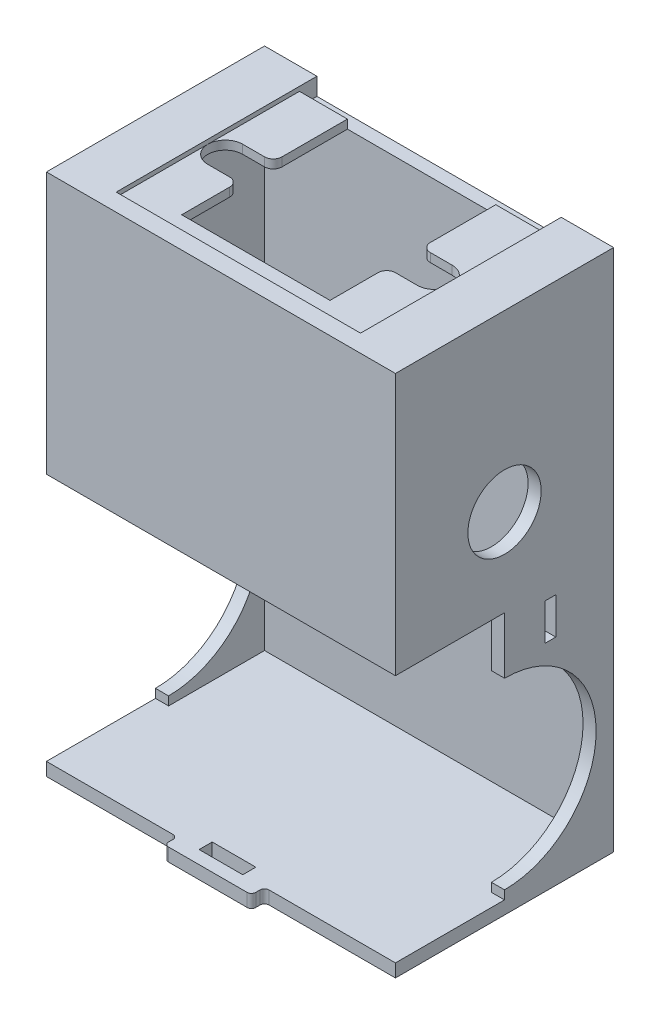
SolidWorks part; units mm, degrees
ref_plane "前视基准面" through (0, 0, 0) normal (0, 0, 1) x (1, 0, 0)
ref_plane "上视基准面" through (0, 0, 0) normal (0, 1, 0) x (1, 0, 0)
ref_plane "右视基准面" through (0, 0, 0) normal (1, 0, 0) x (0, 0, -1)
sketch "草图1" plane through (0, 0, 0) normal (0, 0, 1) x (1, 0, 0)
  line L1 (-20, -30) -> (20, -30)
  line L2 (-20, -30) -> (-20, 30)
  line L3 (-20, 30) -> (20, 30)
  line L4 (20, -30) -> (20, 30)
  line L5 (-20, -30) -> (20, 30) construction
  line L6 (-20, 30) -> (20, -30) construction
  point P0 (0, 0)
  dimension "D1" = 40
  dimension "D2" = 60
extrude "凸台-拉伸1" add sketch "草图1" along normal blind 25
shell "抽壳1" thickness 1.5
sketch "草图2" plane through (20, 0, 0) normal (1, 0, 0) x (0, 0, -1)
  line L0 (-12.5, 30) -> (-12.5, -30) construction
  line L1 (-25, 30) -> (0, 30) construction
  line L2 (-25, -30) -> (0, -30) construction
  circle A0 centre (-12.5, -17) radius 10.5
  dimension "D1" = 13
  dimension "D2" = 21
extrude "切除-拉伸1" cut sketch "草图2" against normal blind 75
sketch "草图3" plane through (0, 0, 25) normal (0, 0, 1) x (1, 0, 0)
  line L0 (20, -30) -> (20, 30) construction
  line L1 (-20, 30) -> (20, 30)
  line L2 (-20, 30) -> (-20, 0)
  line L3 (-20, 0) -> (20, 0)
  line L4 (20, 30) -> (20, 0)
  line L5 (-20, 30) -> (20, 0) construction
  line L6 (-20, 0) -> (20, 30) construction
  line L7 (-20, -30) -> (20, -30) construction
  point P4 (0, 15)
  dimension "D1" = 30
extrude "凸台-拉伸2" add sketch "草图3" against normal blind 1
sketch "草图4" plane through (0, 0, 25) normal (0, 0, 1) x (1, 0, 0)
  line L0 (-20, 30) -> (-20, -30) construction
  line L1 (-20, 0) -> (20, 0)
  line L2 (-20, 0) -> (-20, -28.5)
  line L3 (-20, -28.5) -> (20, -28.5)
  line L4 (20, 0) -> (20, -28.5)
  line L5 (-20, 0) -> (20, -28.5) construction
  line L6 (-20, -28.5) -> (20, 0) construction
  line L7 (20, -30) -> (20, 30) construction
  line L8 (-18.5, 0) -> (18.5, 0) construction
  point P4 (0, -14.25)
  dimension "D1" = 28.5
extrude "切除-拉伸2" cut sketch "草图4" against normal blind 12.5
sketch "草图5" plane through (0, 30, 0) normal (0, 1, 0) x (1, 0, 0)
  line L0 (-30, -12.5) -> (20, -12.5) construction
  line L1 (20, -25) -> (20, 0) construction
  line L3 (20, 0) -> (-20, 0) construction
  circle A1 centre (-20, -12.5) radius 4.2
  circle A2 centre (20, -12.5) radius 4.2
  dimension "D1" = 20
  dimension "D2" = 20
  dimension "D3" = 12.5
extrude "切除-拉伸3" cut sketch "草图5" against normal blind 1.5
sketch "草图6" plane through (0, 30, 0) normal (0, 1, 0) x (1, 0, 0)
  line L0 (0, 5) -> (0, -21) construction
  line L2 (-15.8, -12.5) -> (15.8, -12.5) construction
  line L4 (-14, -21) -> (14, -21)
  line L5 (-14, -21) -> (-14, 5)
  line L6 (-14, 5) -> (14, 5)
  line L7 (14, -21) -> (14, 5)
  line L8 (-14, -21) -> (14, 5) construction
  line L9 (-14, 5) -> (14, -21) construction
  circle A0 centre (0, -12.5) radius 7.5 construction
  circle A1 centre (-20, -12.5) radius 4.2 construction
  circle A2 centre (20, -12.5) radius 4.2 construction
  point P2 (0, -8)
  dimension "D1" = 15
  dimension "D4" = 26
  dimension "D2" = 8.5
  dimension "D5" = 28
extrude "切除-拉伸4" cut sketch "草图6" against normal blind 0.5
sketch "草图8" plane through (0, 29.5, 0) normal (0, 1, 0) x (1, 0, 0)
  line L0 (0, -21) -> (0, 0) construction
  line L1 (-14, -21) -> (14, -21) construction
  line L2 (-15.8, -12.5) -> (15.8, -12.5) construction
  line L3 (5, -12.5) -> (12, -12.5) construction
  line L4 (-8.5, -4) -> (8.5, -4)
  line L5 (-8.5, -4) -> (-8.5, -10.5)
  line L6 (-8.5, -21) -> (8.5, -21)
  line L7 (8.5, -4) -> (8.5, -10.5)
  line L8 (-8.5, -4) -> (8.5, -21) construction
  line L9 (-8.5, -21) -> (8.5, -4) construction
  line L10 (8.5, -10.5) -> (12, -10.5)
  line L11 (8.5, -14.5) -> (12, -14.5)
  line L12 (8.5, -14.5) -> (8.5, -21)
  line L13 (-8.5, -14.5) -> (-12, -14.5)
  line L14 (-8.5, -10.5) -> (-12, -10.5)
  line L15 (-8.5, -14.5) -> (-8.5, -21)
  circle A0 centre (-20, -12.5) radius 4.2 construction
  circle A1 centre (20, -12.5) radius 4.2 construction
  arc A2 (-12, -14.5) -> (-12, -10.5) centre (-12, -12.5) cw
  arc A3 (12, -14.5) -> (12, -10.5) centre (12, -12.5) ccw
  point P11 (0, -12.5)
  point P18 (8.5, -12.5)
  point P28 (-8.5, -12.5)
  dimension "D3" = 2
  dimension "D1" = 17
  dimension "D2" = 3.5
extrude "切除-拉伸7" cut sketch "草图8" against normal blind 3.5
sketch "草图9" plane through (0, 30, 0) normal (0, 1, 0) x (1, 0, 0)
  line L1 (-14, -21) -> (14, -21)
  line L2 (-14, -21) -> (-14, -23)
  line L3 (-14, -23) -> (14, -23)
  line L4 (14, -21) -> (14, -23)
  line L5 (-14, -21) -> (14, -23) construction
  line L6 (-14, -23) -> (14, -21) construction
  point P4 (0, -22)
extrude "切除-拉伸8" cut sketch "草图9" against normal blind 0.5
fillet "圆角1" radius 1 4 edges at (8.5, 29, 14.5) (8.5, 29, 10.5) (-8.5, 29, 14.5) (-8.5, 29, 10.5)
sketch "草图10" plane through (0, 29.5, 0) normal (0, 1, 0) x (1, 0, 0)
  line L0 (8.5, -4) -> (8.5, -2)
  line L1 (14, -23) -> (14, -12.5) construction
  line L2 (-8.5, 0) -> (-14, 0)
  line L3 (-14, 0) -> (-14, -2)
  line L4 (-14, -2) -> (-8.5, -2)
  line L5 (0, 0) -> (0, -2) construction
  line L6 (14, -12.5) -> (8.5, -1) construction
  line L8 (14, -1) -> (8.5, -12.5) construction
  line L9 (14, 0) -> (-14, 0) construction
  line L10 (14, 0) -> (8.5, -2) construction
  line L11 (-14, 0) -> (-14, -23) construction
  line L12 (-8.5, -4) -> (8.5, -4)
  line L13 (-8.5, -4) -> (-8.5, -2)
  line L14 (-8.5, 0) -> (8.5, 0)
  line L15 (14, -2) -> (8.5, 0) construction
  line L16 (-8.5, -4) -> (8.5, 0) construction
  line L17 (-8.5, 0) -> (8.5, -4) construction
  line L19 (14, -2) -> (8.5, -2)
  line L20 (14, 0) -> (14, -2)
  line L21 (8.5, 0) -> (14, 0)
  line L22 (-14, -2) -> (-8.5, 0) construction
  line L23 (-14, 0) -> (-8.5, -2) construction
  arc A1 (12, -14.5) -> (14, -12.5) centre (12, -12.5) ccw construction
  point P4 (11.25, -6.75)
  point P16 (0, -2)
  point P22 (-11.25, -1)
  point P30 (11.25, -1)
extrude "切除-拉伸9" cut sketch "草图10" against normal blind 1.5
sketch "草图17" plane through (20, 0, 0) normal (1, 0, 0) x (0, 0, -1)
  line L0 (-12.5, 0) -> (-12.5, 32.155) construction
  line L4 (-12.5, 0) -> (-25, 0) construction
  circle A1 centre (-12.5, 10) radius 4.2
  dimension "D1" = 10
  dimension "D2" = 8.4
sketch "草图18" plane through (0, 0, 25) normal (0, 0, 1) x (1, 0, 0)
  line L0 (-20, -29.25) -> (20, -29.25) construction
  line L1 (-20, -28.5) -> (-20, -30) construction
  line L2 (20, -30) -> (20, -28.5) construction
  line L3 (-20, -28.5) -> (20, -28.5) construction
  line L4 (-5, -30) -> (5, -30)
  line L5 (-5, -30) -> (-5, -28.5)
  line L6 (-5, -28.5) -> (5, -28.5)
  line L7 (5, -30) -> (5, -28.5)
  line L8 (-5, -30) -> (5, -28.5) construction
  line L9 (-5, -28.5) -> (5, -30) construction
  point P6 (0, -29.25)
extrude "凸台-拉伸6" add sketch "草图18" along normal blind 1.5
sketch "草图22" plane through (0, -28.5, 0) normal (0, 1, 0) x (1, 0, 0)
  line L0 (5, -26.5) -> (-5, -26.5) construction
  line L1 (-2.5, -25) -> (2.5, -25)
  line L2 (-2.5, -25) -> (-2.5, -23.5)
  line L3 (-2.5, -23.5) -> (2.5, -23.5)
  line L4 (2.5, -25) -> (2.5, -23.5)
  line L5 (-2.5, -25) -> (2.5, -23.5) construction
  line L6 (-2.5, -23.5) -> (2.5, -25) construction
  point P0 (0, -24.25)
  point P7 (0, -26.5)
  dimension "D1" = 1.5
  dimension "D2" = 5
  dimension "D3" = 0
  dimension "D4" = 1.5
extrude "切除-拉伸13" cut sketch "草图22" against normal blind 2
fillet "圆角4" radius 0.5 4 edges at (5, -29.25, 25) (-5, -29.25, 25) (5, -29.25, 26.5) (-5, -29.25, 26.5)
sketch "草图26" plane through (20, 0, 0) normal (1, 0, 0) x (0, 0, -1)
  line L0 (-12.5, -3.25) -> (-4.7338, -3.25) construction
  line L1 (-12.5, -6.5) -> (-12.5, 0) construction
  line L3 (-7.875, -5.35) -> (-6.625, -5.35)
  line L4 (-7.875, -5.35) -> (-7.875, -1.15)
  line L5 (-7.875, -1.15) -> (-6.625, -1.15)
  line L6 (-6.625, -5.35) -> (-6.625, -1.15)
  line L7 (-7.875, -5.35) -> (-6.625, -1.15) construction
  line L8 (-7.875, -1.15) -> (-6.625, -5.35) construction
  point P4 (-7.25, -3.25)
  dimension "D1" = 5.25
extrude "切除-拉伸15" cut sketch "草图26" against normal blind 41
fillet "圆角5" radius 0.2 8 edges at (18.5, -1.15, 7.25) (18.5, -5.35, 7.25) (18.5, -3.25, 6.625) (18.5, -3.25, 7.875) (-18.5, -5.35, 7.25) (-18.5, -3.25, 6.625) (-18.5, -3.25, 7.875) (-18.5, -1.15, 7.25)
extrude "切除-拉伸16" cut sketch "草图17" against normal blind 41
sketch "草图27" plane through (0, 28.5, 0) normal (0, 1, 0) x (1, 0, 0)
  line L0 (-20, -8.3) -> (-20, -16.7)
  line L1 (20, -8.3) -> (20, -16.7)
  arc A0 (20, -8.3) -> (20, -16.7) centre (20, -12.5) ccw
  arc A1 (-20, -16.7) -> (-20, -8.3) centre (-20, -12.5) ccw
extrude "凸台-拉伸9" add sketch "草图27" along normal up to surface (1.5 mm away) up to face at (0, 30, 12.1667)
